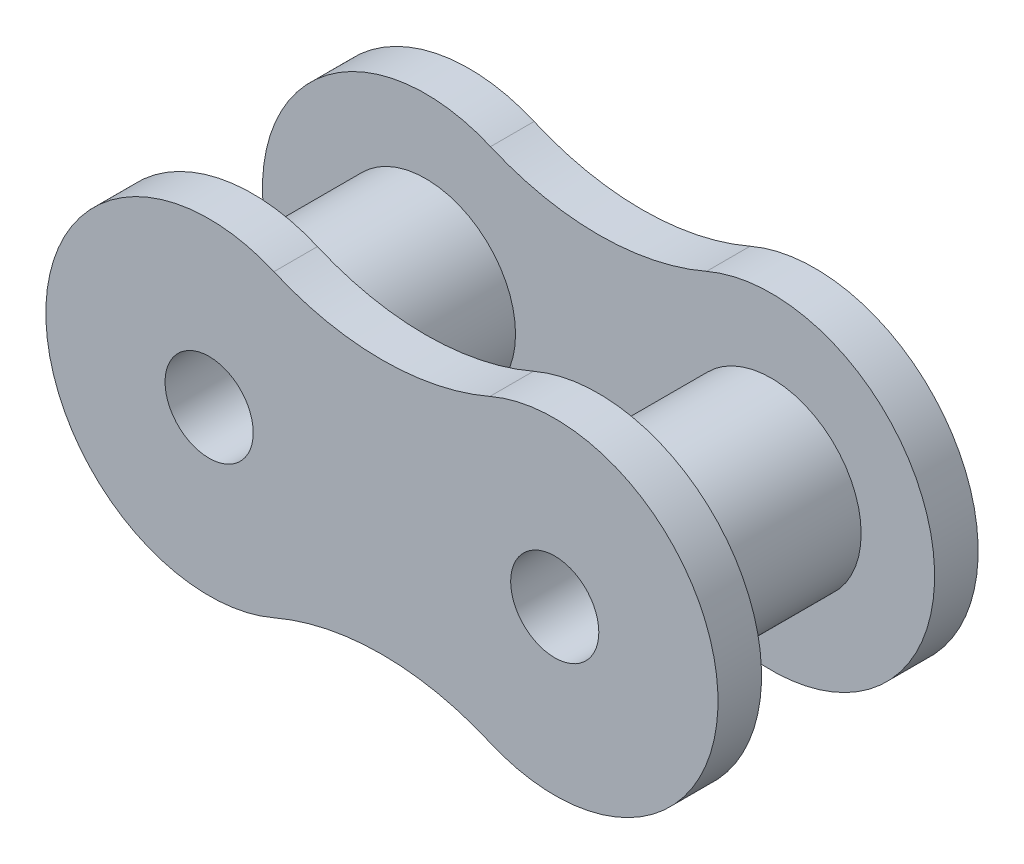
SolidWorks part; units mm, degrees
material "合金钢"
ref_plane "前视基准面" through (0, 0, 0) normal (0, 0, 1) x (1, 0, 0)
ref_plane "上视基准面" through (0, 0, 0) normal (0, 1, 0) x (1, 0, 0)
ref_plane "右视基准面" through (0, 0, 0) normal (1, 0, 0) x (0, 0, -1)
sketch "草图1" plane through (0, 0, 0) normal (0, 0, 1) x (1, 0, 0)
  line L0 (0, 0) -> (6.35, 0) construction
  line L1 (0, 0) -> (1.0014, 0) construction
  line L2 (1.0014, 0) -> (1.0014, 2.8279) construction
  line L3 (6.35, 0) -> (5.35, 0) construction
  line L4 (5.35, 0) -> (5.35, 2.8284) construction
  arc A0 (1.1906, 2.7536) -> (1.1906, -2.7536) centre (0, 0) ccw
  arc A1 (5.1594, -2.7536) -> (5.1594, 2.7536) centre (6.35, 0) ccw
  arc A2 (1.1906, 2.7536) -> (5.1594, 2.7536) centre (3.175, 7.343) ccw
  arc A3 (1.1906, -2.7536) -> (5.1594, -2.7536) centre (3.175, -7.343) cw
  dimension "D1" = 6
  dimension "D3" = 6
  dimension "D2" = 6.35
  dimension "D4" = 1
extrude "凸台-拉伸1" add sketch "草图1" along normal blind 0.8
sketch "草图2" plane through (0, 0, 0) normal (0, 0, -1) x (-1, 0, 0)
  circle A0 centre (-6.35, 0) radius 1.65
  circle A1 centre (0, 0) radius 1.65
  dimension "D1" = 3.3
  dimension "D2" = 3.3
extrude "凸台-拉伸2" add sketch "草图2" along normal blind 3.18
sketch "草图3" plane through (0, 0, -3.18) normal (0, 0, -1) x (-1, 0, 0)
  arc A0 (-1.1906, -2.7536) -> (-5.1594, -2.7536) centre (-3.175, -7.343) ccw construction
  arc A1 (-1.1906, -2.7536) -> (-1.1906, 2.7536) centre (0, 0) ccw construction
  arc A2 (-5.1594, 2.7536) -> (-1.1906, 2.7536) centre (-3.175, 7.343) ccw construction
  arc A3 (-5.1594, 2.7536) -> (-5.1594, -2.7536) centre (-6.35, 0) ccw construction
  arc A4 (-1.1906, -2.7536) -> (-5.1594, -2.7536) centre (-3.175, -7.343) ccw
  arc A5 (-1.1906, -2.7536) -> (-1.1906, 2.7536) centre (0, 0) ccw
  arc A6 (-5.1594, 2.7536) -> (-1.1906, 2.7536) centre (-3.175, 7.343) ccw
  arc A7 (-5.1594, 2.7536) -> (-5.1594, -2.7536) centre (-6.35, 0) ccw
extrude "凸台-拉伸3" add sketch "草图3" along normal blind 0.8
sketch "草图5" plane through (0, 0, -3.98) normal (0, 0, -1) x (-1, 0, 0)
  circle A0 centre (-6.35, 0) radius 0.81
  circle A1 centre (0, 0) radius 0.81
  dimension "D1" = 1.62
  dimension "D2" = 1.62
extrude "切除-拉伸1" cut sketch "草图5" against normal blind 4.8
